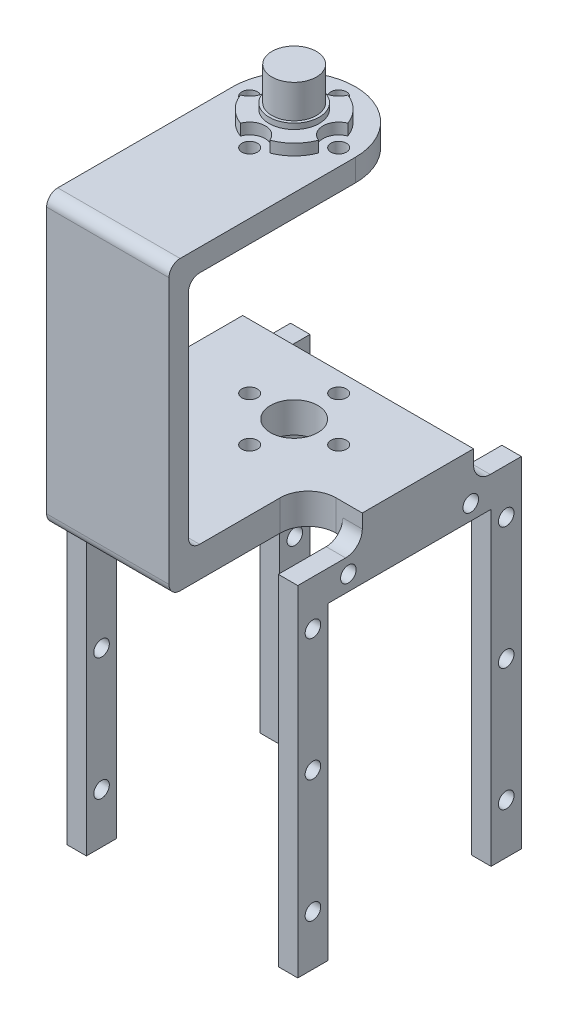
SolidWorks part; units mm, degrees
ref_plane "Front Plane" through (0, 0, 0) normal (0, 0, 1) x (1, 0, 0)
ref_plane "Top Plane" through (0, 0, 0) normal (0, 1, 0) x (1, 0, 0)
ref_plane "Right Plane" through (0, 0, 0) normal (1, 0, 0) x (0, 0, -1)
sketch "Sketch1" plane through (0, 0, 0) normal (0, 1, 0) x (1, 0, 0)
  circle A0 centre (0, 0) radius 11
  circle A1 centre (0, 0) radius 4.25
  dimension "D1" = 22
  dimension "D2" = 8.5
extrude "Boss-Extrude1" add sketch "Sketch1" along normal blind 4
sketch "Sketch2" plane through (0, 4, 0) normal (0, 1, 0) x (1, 0, 0)
  circle A0 centre (0, 8) radius 1.4
  circle A1 centre (8, 0) radius 1.4
  circle A2 centre (0, -8) radius 1.4
  circle A3 centre (-8, 0) radius 1.4
  point P19 (0, 0)
  dimension "D1" = 2.8
  dimension "D2" = 8
  dimension "D3" = 4
extrude "Cut-Extrude1" cut sketch "Sketch2" against normal through all
sketch "Sketch3" plane through (0, 4, 0) normal (0, 1, 0) x (1, 0, 0)
  circle A0 centre (0, 0) radius 7.5
  dimension "D1" = 15
extrude "Boss-Extrude2" add sketch "Sketch3" along normal blind 2
sketch "Sketch4" plane through (0, 6, 0) normal (0, 1, 0) x (1, 0, 0)
  circle A0 centre (8, 0) radius 2.8111
  circle A1 centre (0, -8) radius 2.8111
  circle A2 centre (-8, 0) radius 2.8111
  circle A3 centre (0, 8) radius 2.8111
  point P12 (0, 0)
  dimension "D1" = 4
extrude "Cut-Extrude2" cut sketch "Sketch4" against normal up to surface (2 mm away) up to face at (0, 4, 0)
sketch "Sketch5" plane through (0, 6, 0) normal (0, 1, 0) x (1, 0, 0)
  circle A0 centre (0, 0) radius 4.5
  dimension "D1" = 9
extrude "Boss-Extrude3" add sketch "Sketch5" along normal blind 7
sketch "Sketch6" plane through (0, 13, 0) normal (0, 1, 0) x (1, 0, 0)
  circle A0 centre (0, 0) radius 4
  circle A1 centre (0, 0) radius 4.5
  dimension "D1" = 8
extrude "Cut-Extrude3" cut sketch "Sketch6" against normal blind 6
sketch "Sketch8" plane through (0, 0, 0) normal (0, -1, 0) x (1, 0, 0)
  line L0 (-11, 30) -> (-11, 0)
  line L1 (-11, 30) -> (11, 30)
  line L2 (11, 30) -> (11, 0)
  circle A0 centre (0, 0) radius 11 construction
  circle A1 centre (0, 0) radius 11
  point P4 (0, 0)
  circle M7 centre (0, 0) radius 11
  dimension "D2" = 30
extrude "Boss-Extrude4" add sketch "Sketch8" against normal up to surface (4 mm away) contours L2 L1 L0 M7 up to face at (0, 4, 0)
sketch "Sketch11" plane through (-11, 0, 0) normal (-1, 0, 0) x (0, 0, 1)
  line L0 (30, 4) -> (30, 0) construction
  line L1 (0, 0) -> (30, 0)
  line L2 (0, 0) -> (0, 1)
  line L3 (0, 1) -> (30, 1)
  line L4 (30, 0) -> (30, 1)
  line L5 (15, 1) -> (15, 0) construction
  line L6 (0, 0.5) -> (30, 0.5) construction
  point P108 (15, 0.5)
  dimension "D1" = 1
sketch "Sketch13" plane through (0, 4, 0) normal (0, 1, 0) x (1, 0, 0)
  line L1 (-11, -30) -> (11, -30)
  line L2 (-11, -30) -> (-11, -33.5)
  line L3 (-11, -33.5) -> (11, -33.5)
  line L4 (11, -30) -> (11, -33.5)
  line L5 (0, -33.5) -> (0, -30) construction
  line L6 (-11, -31.75) -> (11, -31.75) construction
  point P4 (11, -15)
  point P700 (0, -31.75)
  dimension "D1" = 3.5
extrude "Boss-Extrude5" add sketch "Sketch13" against normal blind 46.25
sketch "Sketch14" plane through (0, 0, 33.5) normal (0, 0, 1) x (1, 0, 0)
  line L1 (-11, -42.25) -> (11, -42.25)
  line L2 (-11, -42.25) -> (-11, -47.75)
  line L3 (-11, -47.75) -> (11, -47.75)
  line L4 (11, -42.25) -> (11, -47.75)
  line L5 (0, -47.75) -> (0, -42.25) construction
  line L6 (-11, -45) -> (11, -45) construction
  point P4 (11, -40.75)
  point P452 (0, -45)
  dimension "D1" = 5.5
extrude "Boss-Extrude6" add sketch "Sketch14" against normal blind 45
sketch "Sketch16" plane through (0, -47.75, 0) normal (0, -1, 0) x (1, 0, 0)
  circle A2 centre (0, 0) radius 4.25 construction
  circle A3 centre (0, 0) radius 4.25
  circle A4 centre (-8, 0) radius 1.4 construction
  circle A5 centre (0, -8) radius 1.4 construction
  circle A6 centre (8, 0) radius 1.4 construction
  circle A7 centre (0, 8) radius 1.4 construction
  circle A8 centre (-8, 0) radius 1.4
  circle A9 centre (0, -8) radius 1.4
  circle A10 centre (8, 0) radius 1.4
  circle A11 centre (0, 8) radius 1.4
extrude "Cut-Extrude6" cut sketch "Sketch16" against normal blind 30
sketch "Sketch17" plane through (0, 0, -11.5) normal (0, 0, -1) x (-1, 0, 0)
  line L0 (0, 4) -> (0, -47.75) construction
  line L1 (-20.75, -42.25) -> (-11, -42.25)
  line L2 (-20.75, -42.25) -> (-20.75, -47.75)
  line L3 (-20.75, -47.75) -> (-11, -47.75)
  line L4 (-11, -42.25) -> (-11, -47.75)
  line L5 (-15.875, -47.75) -> (-15.875, -42.25) construction
  line L6 (-20.75, -45) -> (-11, -45) construction
  line L7 (11, -47.75) -> (-11, -47.75) construction
  line L8 (20.75, -45) -> (11, -45) construction
  line L9 (15.875, -47.75) -> (15.875, -42.25) construction
  line L10 (11, -42.25) -> (11, -47.75)
  line L11 (20.75, -47.75) -> (11, -47.75)
  line L12 (20.75, -42.25) -> (20.75, -47.75)
  line L13 (20.75, -42.25) -> (11, -42.25)
  point P16 (15.875, -45)
  point P268 (-15.875, -45)
  dimension "D1" = 41.5
extrude "Boss-Extrude7" add sketch "Sketch17" against normal blind 20
fillet "Fillet3" radius 2 4 edges at (0, 0, 30) (0, 4, 33.5) (0, -47.75, 33.5) (0, -42.25, 30)
sketch "Sketch19" plane through (0, -47.75, 0) normal (0, -1, 0) x (1, 0, 0)
  circle A0 centre (-8, 0) radius 2.5
  circle A1 centre (0, 8) radius 2.5
  circle A2 centre (8, 0) radius 2.5
  circle A3 centre (0, -8) radius 2.5
  point P12 (0, 0)
  dimension "D1" = 5
  dimension "D2" = 4
extrude "Cut-Extrude8" cut sketch "Sketch19" against normal blind 1.5
sketch "Sketch21" plane through (0, -47.75, 0) normal (0, -1, 0) x (1, 0, 0)
  line L0 (-17.25, 20.1) -> (-20.75, 20.1)
  line L1 (-17.25, 20.1) -> (17.25, 20.1) construction
  line L2 (-17.25, 20.1) -> (-17.25, -20.1)
  line L3 (-17.25, -20.1) -> (17.25, -20.1) construction
  line L4 (17.25, 20.1) -> (17.25, -20.1)
  line L5 (0, -20.1) -> (0, 20.1) construction
  line L6 (-17.25, 0) -> (17.25, 0) construction
  line L7 (-20.75, 20.1) -> (-20.75, -20.1)
  line L8 (-20.75, -20.1) -> (-17.25, -20.1)
  line L9 (17.25, 20.1) -> (20.75, 20.1)
  line L10 (20.75, 20.1) -> (20.75, -20.1)
  line L11 (20.75, -20.1) -> (17.25, -20.1)
  point P368 (0, 0)
  dimension "D1" = 34.5
  dimension "D2" = 40.2
  dimension "D3" = 3.5
extrude "Boss-Extrude8" add sketch "Sketch21" along normal blind 61.1
sketch "Sketch22" plane through (20.75, 0, 0) normal (1, 0, 0) x (0, 0, -1)
  line L0 (-14.65, -108.85) -> (-14.65, -53.25)
  line L1 (20.1, -108.85) -> (-20.1, -108.85) construction
  line L2 (-14.65, -53.25) -> (14.65, -53.25)
  line L3 (14.65, -53.25) -> (14.65, -108.85)
  line L4 (14.65, -108.85) -> (-14.65, -108.85)
  line L5 (-20.1, -108.85) -> (-14.65, -108.85) construction
  line L7 (-8.5, -47.75) -> (11.5, -47.75) construction
  line L8 (0, -53.25) -> (0, -47.75) construction
  circle A0 centre (-11, -50.5) radius 1.4
  circle A1 centre (11, -50.5) radius 1.4
  circle A2 centre (-17.375, -99.85) radius 1.4
  circle A3 centre (-17.375, -77.85) radius 1.4
  circle A4 centre (-17.375, -55.85) radius 1.4
  circle A5 centre (17.375, -99.85) radius 1.4
  circle A6 centre (17.375, -77.85) radius 1.4
  circle A7 centre (17.375, -55.85) radius 1.4
  point P7 (0, -108.85)
  point P8 (0, -108.85)
  point P11 (0, -50.5)
  point P25 (-17.375, -108.85)
  dimension "D3" = 2.8
  dimension "D4" = 22
  dimension "D5" = 2.8
  dimension "D7" = 3
  dimension "D1" = 29.3
  dimension "D2" = 55.6
  dimension "D6" = 9
extrude "Cut-Extrude10" cut sketch "Sketch22" against normal blind 61.1
fillet "Fillet4" radius 5 2 edges at (-11, -45, 8.5) (11, -45, 8.5)
fillet "Fillet5" radius 3 4 edges at (19, -47.75, 8.5) (-19, -47.75, 8.5) (19, -47.75, -11.5) (-19, -47.75, -11.5)
